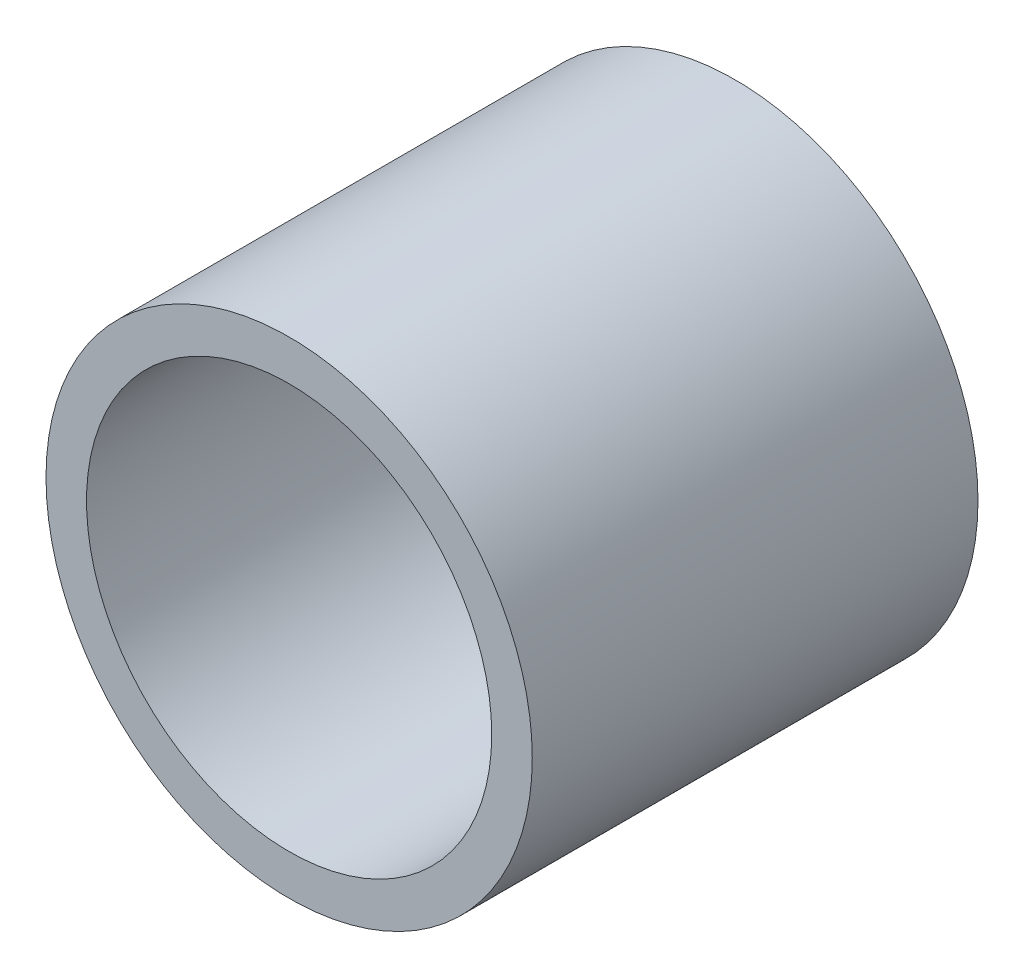
SolidWorks part; units mm, degrees
material "6061 合金"
ref_plane "前视基准面" through (0, 0, 0) normal (0, 0, 1) x (1, 0, 0)
ref_plane "上视基准面" through (0, 0, 0) normal (0, 1, 0) x (1, 0, 0)
ref_plane "右视基准面" through (0, 0, 0) normal (1, 0, 0) x (0, 0, -1)
other "Configuration Table"
sketch "草图1" plane through (0, 0, 0) normal (0, 0, 1) x (1, 0, 0)
  circle A0 centre (0, 0) radius 5
  circle A1 centre (0, 0) radius 6
  dimension "D1" = 10
  dimension "D2" = 12
extrude "凸台-拉伸1" add sketch "草图1" along normal blind 11 contours A0 | A1
sketch "草图2" plane through (0, 0, 0) normal (0, 0, -1) x (-1, 0, 0)
  circle A0 centre (0, 0) radius 7
  circle A1 centre (0, 0) radius 5 construction
  circle A2 centre (0, 0) radius 5
  dimension "D1" = 14
extrude "凸台-拉伸2" [suppressed] add sketch "草图2" against normal blind 1
sketch "草图3" [suppressed] plane through (0, 0, 15) normal (0, 0, 1) x (1, 0, 0)
  circle A1 centre (0, 0) radius 5 construction
  circle A2 centre (0, 0) radius 5
  circle A3 centre (0, 0) radius 7 construction
  circle A4 centre (0, 0) radius 7
extrude "凸台-拉伸3" [suppressed] add sketch "草图3" against normal blind 1
fillet "圆角1" [suppressed] radius 0.5
chamfer "倒角1" [suppressed] distance 0.5 angle 45
